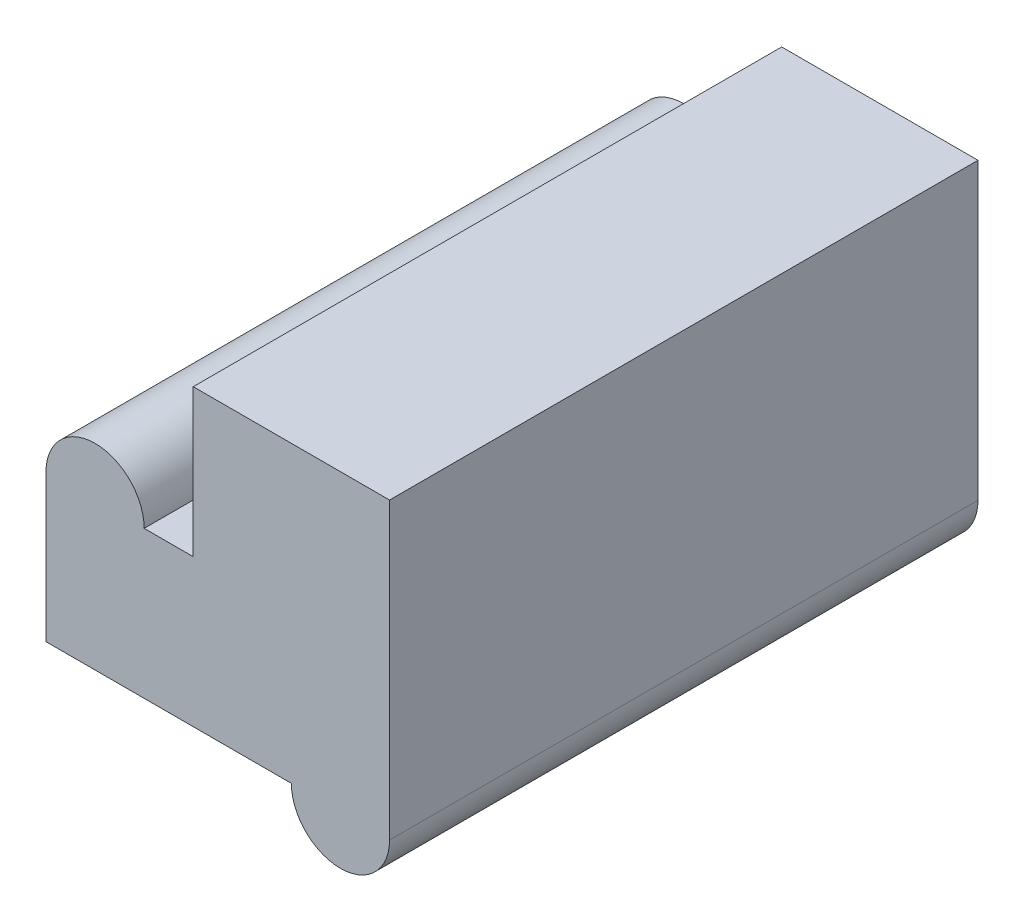
SolidWorks part; units mm, degrees
ref_plane "Front Plane" through (0, 0, 0) normal (0, 0, 1) x (1, 0, 0)
ref_plane "Top Plane" through (0, 0, 0) normal (0, 1, 0) x (1, 0, 0)
ref_plane "Right Plane" through (0, 0, 0) normal (1, 0, 0) x (0, 0, -1)
sketch "First Part " plane through (0, 0, 0) normal (0, 0, 1) x (1, 0, 0)
  line L0 (0, 0) -> (0, 76.2)
  line L1 (0, 76.2) -> (101.6, 76.2)
  line L2 (101.6, 76.2) -> (101.6, -76.2)
  line L3 (50.8, -76.2) -> (-76.2, -76.2)
  line L4 (-76.2, -76.2) -> (-76.2, 0)
  line L5 (-25.4, 0) -> (0, 0)
  arc A0 (101.6, -76.2) -> (50.8, -76.2) centre (76.2, -76.2) cw
  arc A1 (-76.2, 0) -> (-25.4, 0) centre (-50.8, 0) cw
  dimension "D4" = 25.4
  dimension "D7" = 25.4
  dimension "D1" = 101.6
  dimension "D2" = 152.4
  dimension "D3" = 76.2
  dimension "D5" = 76.2
  dimension "D6" = 127
extrude "Boss-Extrude1" add sketch "First Part " along normal blind 140.208 and the other way blind 164.338
